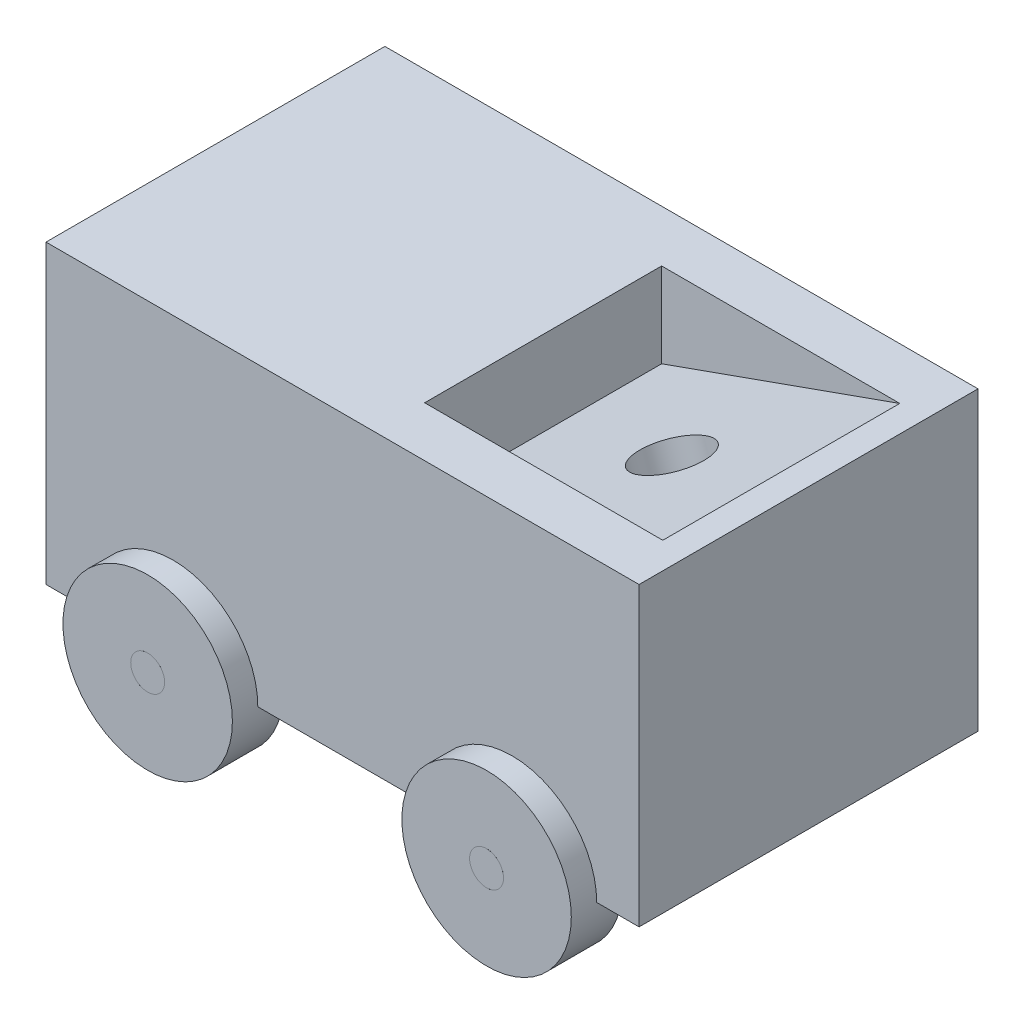
SolidWorks part; units mm, degrees
ref_plane "Front Plane" through (0, 0, 0) normal (0, 0, 1) x (1, 0, 0)
ref_plane "Top Plane" through (0, 0, 0) normal (0, 1, 0) x (1, 0, 0)
ref_plane "Right Plane" through (0, 0, 0) normal (1, 0, 0) x (0, 0, -1)
sketch "Sketch2" plane through (0, 0, 0) normal (0, 0, 1) x (1, 0, 0)
  line L1 (0, 0) -> (-70, 0)
  line L2 (0, 0) -> (0, -35)
  line L3 (0, -35) -> (-70, -35)
  line L4 (-70, 0) -> (-70, -35)
extrude "Boss-Extrude2" add sketch "Sketch2" along normal blind 40
sketch "Sketch3" plane through (0, 0, 0) normal (0, 1, 0) x (1, 0, 0)
  line L1 (-31.2286, -34.0804) -> (-3.1227, -34.0804)
  line L2 (-31.2286, -34.0804) -> (-31.2286, -6.1085)
  line L3 (-31.2286, -6.1085) -> (-3.1227, -6.1085)
  line L4 (-3.1227, -34.0804) -> (-3.1227, -6.1085)
extrude "Cut-Extrude1" cut sketch "Sketch3" against normal blind 10
sketch "Sketch4" plane through (0, 0, 40) normal (0, 0, 1) x (1, 0, 0)
  circle A2 centre (-15, -35) radius 10
  circle A4 centre (-55, -35) radius 10
extrude "Cut-Extrude2" cut sketch "Sketch4" against normal blind 3
sketch "Sketch5" plane through (0, 0, 0) normal (0, 0, -1) x (-1, 0, 0)
  circle A1 centre (15, -35) radius 10
  circle A3 centre (55, -35) radius 10
extrude "Cut-Extrude3" cut sketch "Sketch5" against normal blind 3
sketch "Sketch6" plane through (0, 0, 40) normal (0, 0, 1) x (1, 0, 0)
  circle A0 centre (-55, -35) radius 10
extrude "Boss-Extrude3" add sketch "Sketch6" along normal blind 3 and the other way blind 3
sketch "Sketch7" plane through (0, 0, 3) normal (0, 0, -1) x (-1, 0, 0)
  line L2 (45, -35) -> (65, -35) construction
  circle A2 centre (55, -35) radius 10
extrude "Boss-Extrude5" add sketch "Sketch7" along normal blind 6
sketch "Sketch8" plane through (0, 0, -3) normal (0, 0, -1) x (-1, 0, 0)
  circle A1 centre (55, -35) radius 2
extrude "Cut-Extrude5" cut sketch "Sketch8" against normal blind 46
sketch "Sketch9" plane through (0, 0, -3) normal (0, 0, -1) x (-1, 0, 0)
  circle A0 centre (55, -35) radius 2
extrude "Boss-Extrude8" add sketch "Sketch9" along normal blind 0.0001 and the other way blind 46.0001 contours A0
sketch "Sketch10" plane through (0, 0, 40) normal (0, 0, 1) x (1, 0, 0)
  circle A0 centre (-15, -35) radius 10
extrude "Boss-Extrude9" add sketch "Sketch10" along normal blind 3 and the other way blind 3
sketch "Sketch11" plane through (0, 0, 0) normal (0, 0, -1) x (-1, 0, 0)
  circle A0 centre (15, -35) radius 10
extrude "Boss-Extrude10" add sketch "Sketch11" along normal blind 3 and the other way blind 3
sketch "Sketch12" plane through (0, 0, -3) normal (0, 0, -1) x (-1, 0, 0)
  circle A1 centre (15, -35) radius 2
extrude "Cut-Extrude6" cut sketch "Sketch12" against normal blind 46
sketch "Sketch13" plane through (0, 0, -3) normal (0, 0, -1) x (-1, 0, 0)
  circle A0 centre (15, -35) radius 2
extrude "Boss-Extrude11" add sketch "Sketch13" along normal blind 0.001 and the other way blind 46.001
sketch "Sketch14" plane through (0, 0, 34.0804) normal (0, 0, -1) x (-1, 0, 0)
  line L0 (3.1227, 0) -> (31.2286, -10)
  line L1 (31.2286, -10) -> (3.1227, -10) construction
  line L2 (31.2286, -10) -> (3.1227, -10)
  line L3 (3.1227, -10) -> (3.1227, 0)
extrude "Boss-Extrude12" add sketch "Sketch14" along normal blind 28
sketch "Sketch15" plane through (-0.3509, 0.9862, 0) normal (-0.3352, 0.9421, 0) x (0.9421, 0.3352, 0)
  circle A0 centre (-15.8401, -21.5019) radius 4
sketch "Sketch16" plane through (-0.3509, 0.9862, 0) normal (-0.3352, 0.9421, 0) x (0.9421, 0.3352, 0)
  circle A0 centre (-16.3743, -20.3525) radius 4
sketch "Sketch18" plane through (-0.3509, 0.9862, 0) normal (-0.3352, 0.9421, 0) x (0.9421, 0.3352, 0)
  circle A1 centre (-16.3743, -20.3525) radius 4
extrude "Cut-Extrude11" cut sketch "Sketch18" against normal blind 10
